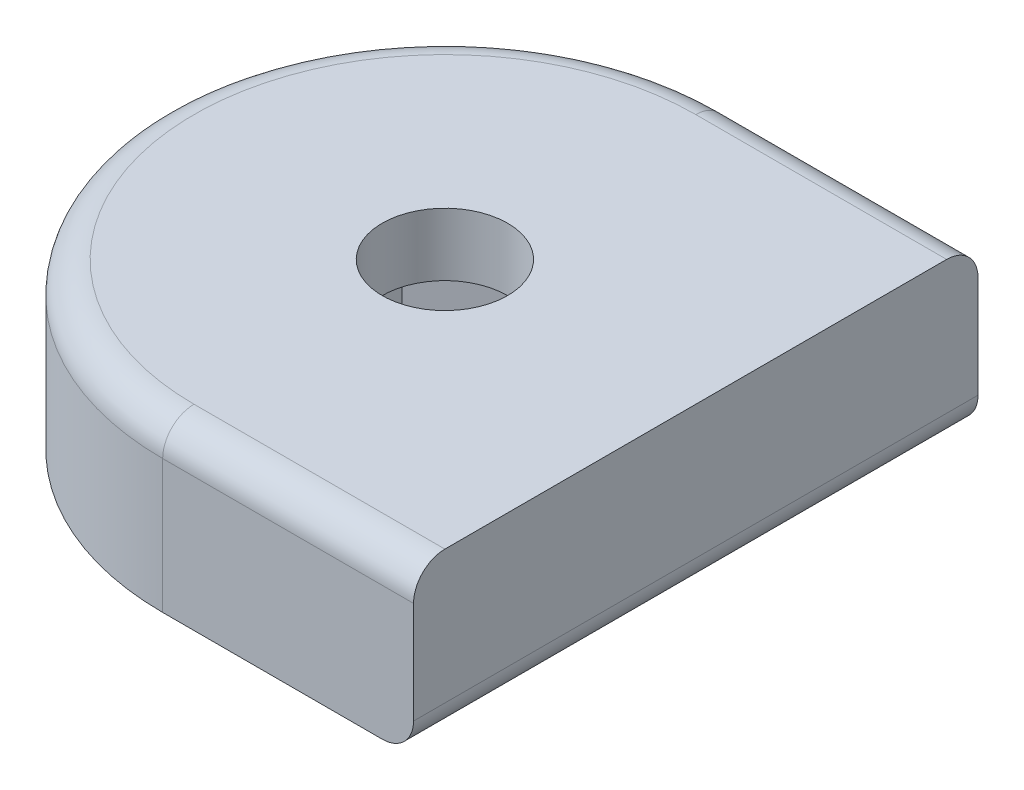
SolidWorks part; units mm, degrees
ref_plane "Plan de face" through (0, 0, 0) normal (0, 0, 1) x (1, 0, 0)
ref_plane "Plan de dessus" through (0, 0, 0) normal (0, 1, 0) x (1, 0, 0)
ref_plane "Plan de droite" through (0, 0, 0) normal (1, 0, 0) x (0, 0, -1)
sketch "Esquisse1" plane through (0, 0, 0) normal (0, 1, 0) x (1, 0, 0)
  line L0 (0, 18) -> (16, 18)
  line L1 (16, 18) -> (16, -18)
  line L2 (16, -18) -> (0, -18)
  arc A0 (0, -18) -> (0, 18) centre (0, 0) cw
  dimension "D2" = 18
  dimension "D1" = 16
extrude "Boss.-Extru.1" add sketch "Esquisse1" along normal blind 10.5
sketch "Esquisse2" plane through (0, 0, 0) normal (0, 1, 0) x (1, 0, 0)
  line L1 (0, -7.5056) -> (6.5, -3.7528)
  line L2 (6.5, -3.7528) -> (6.5, 3.7528)
  line L3 (6.5, 3.7528) -> (0, 7.5056)
  line L4 (0, 7.5056) -> (-6.5, 3.7528)
  line L5 (-6.5, 3.7528) -> (-6.5, -3.7528)
  line L6 (-6.5, -3.7528) -> (0, -7.5056)
  circle A0 centre (0, 0) radius 6.5 construction
  dimension "D1" = 13
extrude "Enlèv. mat.-Extru.1" cut sketch "Esquisse2" along normal blind 6.5
sketch "Esquisse3" plane through (0, 6.5, 0) normal (0, -1, 0) x (-1, 0, 0)
  circle A0 centre (0, 0) radius 4
  dimension "D1" = 8
extrude "Enlèv. mat.-Extru.2" cut sketch "Esquisse3" against normal through all
fillet "Congé1" radius 2 4 edges at (8, 10.5, -18) (8, 10.5, 18) (-18, 10.5, 0) (16, 0, 0)
